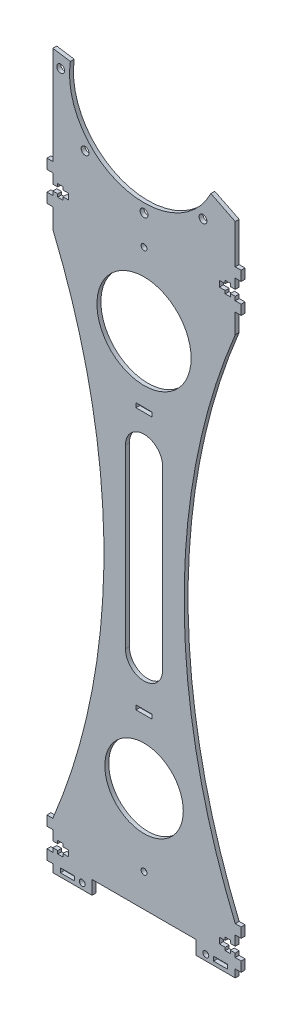
SolidWorks part; units mm, degrees
ref_plane "前视基准面" through (0, 0, 0) normal (0, 0, 1) x (1, 0, 0)
ref_plane "上视基准面" through (0, 0, 0) normal (0, 1, 0) x (1, 0, 0)
ref_plane "右视基准面" through (0, 0, 0) normal (1, 0, 0) x (0, 0, -1)
sketch "草图3" plane through (0, 0, 0) normal (0, 0, 1) x (1, 0, 0)
  line L0 (-42.5, -1.9902) -> (-42.5, -2.0902) construction
  line L2 (-46.5, -1.9902) -> (-46.5, 0.0098) construction
  line L4 (46.5, -1.9902) -> (46.5, 0.0098) construction
  line L5 (-42.5, 0.0098) -> (-35.5, 0.0098) construction
  line L6 (-42.5, 0.0098) -> (-42.5, -1.9902) construction
  line L7 (-42.5, -1.9902) -> (-35.5, -1.9902) construction
  line L8 (-35.5, 0.0098) -> (-35.5, -1.9902) construction
  line L9 (-42.5, -2.0902) -> (-42.6, -2.0902) construction
  line L10 (0, 113.3559) -> (0, 203.3559) construction
  line L11 (35.5, 0.0098) -> (42.5, 0.0098) construction
  line L12 (35.5, 0.0098) -> (35.5, -1.9902) construction
  line L13 (35.5, -1.9902) -> (42.5, -1.9902) construction
  line L14 (42.5, 0.0098) -> (42.5, -1.9902) construction
  line L15 (-46.5, 360.0098) -> (-46.5, 310.0098)
  line L17 (0, 308.5098) -> (0, 282.3462) construction
  line L18 (0, 36.4782) -> (0, 3.0098) construction
  line L19 (-42.6, -2.0902) -> (-35.4, -2.0902)
  line L20 (-42.6, -2.0902) -> (-42.6, 0.1098)
  line L21 (-42.6, 0.1098) -> (-35.4, 0.1098)
  line L22 (-35.4, -2.0902) -> (-35.4, 0.1098)
  line L23 (35.4, -2.0902) -> (35.4, 0.1098)
  line L24 (42.6, -2.0902) -> (35.4, -2.0902)
  line L25 (42.6, -2.0902) -> (42.6, 0.1098)
  line L26 (42.6, 0.1098) -> (35.4, 0.1098)
  line L27 (-46.5, 0.0098) -> (-46.5, -3.9902)
  line L28 (-46.5, -3.9902) -> (-26.5, -3.9902)
  line L29 (-26.5, -3.9902) -> (-26.5, 3.0098)
  line L30 (46.5, 0.0098) -> (46.5, -3.9902)
  line L31 (46.5, -3.9902) -> (26.5, -3.9902)
  line L32 (26.5, -3.9902) -> (26.5, 3.0098)
  line L33 (-26.5, 3.0098) -> (26.5, 3.0098)
  line L37 (46.5, 330.0098) -> (34.0612, 336.1623)
  line L38 (-46.5, 360.0098) -> (-37.5766, 358.6665)
  line L39 (-46.5, 0.0098) -> (-49.5, 0.0098)
  line L40 (-49.5, 0.0098) -> (-49.5, 5.0098)
  line L41 (-49.5, 5.0098) -> (-46.5, 5.0098)
  line L42 (-44, 7.0098) -> (-44, 5.5098)
  line L43 (-44, 10.0098) -> (-44, 11.5098)
  line L44 (-46.5, 10.0098) -> (-44, 10.0098)
  line L45 (-44, 5.5098) -> (-41.4, 5.5098)
  line L46 (-41.4, 5.5098) -> (-41.4, 7.0098)
  line L47 (-41.4, 7.0098) -> (-38.4, 7.0098)
  line L48 (-38.4, 10.0098) -> (-38.4, 7.0098)
  line L49 (-41.4, 10.0098) -> (-38.4, 10.0098)
  line L50 (-41.4, 11.5098) -> (-41.4, 10.0098)
  line L51 (-44, 11.5098) -> (-41.4, 11.5098)
  line L52 (-44, 7.0098) -> (-46.5, 7.0098)
  line L53 (-46.5, 5.0098) -> (-46.5, 7.0098)
  line L54 (-46.5, 10.0098) -> (-46.5, 15.0098)
  line L55 (-46.5, 15.0098) -> (-49.5, 15.0098)
  line L56 (-49.5, 15.0098) -> (-49.5, 20.0098)
  line L59 (49.5, 20.0098) -> (46.5, 20.0098)
  line L60 (49.5, 15.0098) -> (49.5, 20.0098)
  line L61 (46.5, 15.0098) -> (49.5, 15.0098)
  line L62 (46.5, 10.0098) -> (46.5, 15.0098)
  line L63 (46.5, 5.0098) -> (46.5, 7.0098)
  line L64 (44, 7.0098) -> (46.5, 7.0098)
  line L65 (44, 11.5098) -> (41.4, 11.5098)
  line L66 (41.4, 11.5098) -> (41.4, 10.0098)
  line L67 (41.4, 10.0098) -> (38.4, 10.0098)
  line L68 (38.4, 10.0098) -> (38.4, 7.0098)
  line L69 (41.4, 7.0098) -> (38.4, 7.0098)
  line L70 (41.4, 5.5098) -> (41.4, 7.0098)
  line L71 (44, 5.5098) -> (41.4, 5.5098)
  line L72 (46.5, 10.0098) -> (44, 10.0098)
  line L73 (44, 10.0098) -> (44, 11.5098)
  line L74 (44, 7.0098) -> (44, 5.5098)
  line L75 (49.5, 5.0098) -> (46.5, 5.0098)
  line L76 (46.5, 0.0098) -> (49.5, 0.0098)
  line L77 (49.5, 0.0098) -> (49.5, 5.0098)
  line L81 (0, 103.8804) -> (0, 76.4782) construction
  line L84 (-46.5, 290.0098) -> (-49.5, 290.0098)
  line L85 (-49.5, 290.0098) -> (-49.5, 295.0098)
  line L86 (-49.5, 295.0098) -> (-46.5, 295.0098)
  line L87 (-44, 297.0098) -> (-44, 295.5098)
  line L88 (-44, 300.0098) -> (-44, 301.5098)
  line L89 (-46.5, 300.0098) -> (-44, 300.0098)
  line L90 (-44, 295.5098) -> (-41.4, 295.5098)
  line L91 (-41.4, 295.5098) -> (-41.4, 297.0098)
  line L92 (-41.4, 297.0098) -> (-38.4, 297.0098)
  line L93 (-38.4, 300.0098) -> (-38.4, 297.0098)
  line L94 (-41.4, 300.0098) -> (-38.4, 300.0098)
  line L95 (-41.4, 301.5098) -> (-41.4, 300.0098)
  line L96 (-44, 301.5098) -> (-41.4, 301.5098)
  line L97 (-44, 297.0098) -> (-46.5, 297.0098)
  line L98 (-46.5, 295.0098) -> (-46.5, 297.0098)
  line L99 (-46.5, 300.0098) -> (-46.5, 305.0098)
  line L100 (-46.5, 305.0098) -> (-49.5, 305.0098)
  line L101 (-49.5, 305.0098) -> (-49.5, 310.0098)
  line L102 (-49.5, 310.0098) -> (-46.5, 310.0098)
  line L103 (49.5, 310.0098) -> (46.5, 310.0098)
  line L104 (49.5, 305.0098) -> (49.5, 310.0098)
  line L105 (46.5, 305.0098) -> (49.5, 305.0098)
  line L106 (46.5, 300.0098) -> (46.5, 305.0098)
  line L107 (46.5, 295.0098) -> (46.5, 297.0098)
  line L108 (44, 297.0098) -> (46.5, 297.0098)
  line L109 (44, 301.5098) -> (41.4, 301.5098)
  line L110 (41.4, 301.5098) -> (41.4, 300.0098)
  line L111 (41.4, 300.0098) -> (38.4, 300.0098)
  line L112 (38.4, 300.0098) -> (38.4, 297.0098)
  line L113 (41.4, 297.0098) -> (38.4, 297.0098)
  line L114 (41.4, 295.5098) -> (41.4, 297.0098)
  line L115 (44, 295.5098) -> (41.4, 295.5098)
  line L116 (46.5, 300.0098) -> (44, 300.0098)
  line L117 (44, 300.0098) -> (44, 301.5098)
  line L118 (44, 297.0098) -> (44, 295.5098)
  line L119 (49.5, 295.0098) -> (46.5, 295.0098)
  line L120 (49.5, 290.0098) -> (49.5, 295.0098)
  line L121 (46.5, 290.0098) -> (49.5, 290.0098)
  line L122 (46.5, 330.0098) -> (46.5, 310.0098)
  line L123 (46.5, 290.0098) -> (46.5, 280.0098)
  line L124 (-46.5, 290.0098) -> (-46.5, 280.0098)
  line L127 (-49.5, 20.0098) -> (-46.5, 20.0098)
  line L129 (-9.4755, 113.3559) -> (-9.4755, 203.3559)
  line L130 (9.4755, 113.3559) -> (9.4755, 203.3559)
  line L132 (0, 212.8314) -> (0, 234.3433) construction
  line L133 (4.1, 91.2793) -> (-4.1, 91.2793)
  line L134 (4.1, 91.2793) -> (4.1, 89.0793)
  line L135 (4.1, 89.0793) -> (-4.1, 89.0793)
  line L136 (-4.1, 91.2793) -> (-4.1, 89.0793)
  line L137 (4.1, 91.2793) -> (-4.1, 89.0793) construction
  line L138 (4.1, 89.0793) -> (-4.1, 91.2793) construction
  line L140 (4.1, 224.6874) -> (-4.1, 224.6874)
  line L141 (4.1, 224.6874) -> (4.1, 222.4874)
  line L142 (4.1, 222.4874) -> (-4.1, 222.4874)
  line L143 (-4.1, 224.6874) -> (-4.1, 222.4874)
  line L144 (4.1, 224.6874) -> (-4.1, 222.4874) construction
  line L145 (4.1, 222.4874) -> (-4.1, 224.6874) construction
  circle A0 centre (-31.5, -0.9902) radius 1.5
  circle A1 centre (31.5, -0.9902) radius 1.5
  circle A4 centre (0, 310.5098) radius 2
  circle A5 centre (-30.052, 322.9577) radius 2
  circle A6 centre (-42.5, 353.0098) radius 2
  circle A11 centre (30.052, 322.9577) radius 2
  arc A12 (-37.5766, 358.6665) -> (34.0612, 336.1623) centre (0, 353.0098) ccw
  arc A15 (-46.5, 280.0098) -> (-46.5, 20.0098) centre (-357.8256, 150.0098) cw
  arc A16 (46.5, 280.0098) -> (46.5, 20.0098) centre (357.8256, 150.0098) ccw
  circle A17 centre (0, 258.3448) radius 24.0015
  circle A18 centre (0, 56.4782) radius 20
  arc A19 (-9.4755, 113.3559) -> (9.4755, 113.3559) centre (0, 113.3559) ccw
  arc A20 (9.4755, 203.3559) -> (-9.4755, 203.3559) centre (0, 203.3559) ccw
  circle A21 centre (0, 19.744) radius 1.5
  circle A22 centre (0, 295.428) radius 1.5
  point P56 (0, 158.3559)
  point P143 (0, 90.1793)
  point P151 (0, 223.5874)
extrude "凸台-拉伸1" add sketch "草图3" along normal blind 2
sketch "草图4" plane through (46.5, 0, 0) normal (1, 0, 0) x (0, 0, -1)
  line L0 (-2, 10.0098) -> (0, 7.0098)
  circle A0 centre (-1, 8.5098) radius 1.5
sketch "草图5" plane through (-46.5, 0, 0) normal (-1, 0, 0) x (0, 0, 1)
  line L0 (0, 10.0098) -> (2, 7.0098)
  circle A0 centre (1, 8.5098) radius 1.5
sketch "草图6" plane through (46.5, 0, 0) normal (1, 0, 0) x (0, 0, -1)
  line L0 (-2, 300.0098) -> (0, 297.0098)
  circle A0 centre (-1, 298.5098) radius 1.5
sketch "草图7" plane through (-46.5, 0, 0) normal (-1, 0, 0) x (0, 0, 1)
  line L0 (0, 300.0098) -> (2, 297.0098)
  circle A0 centre (1, 298.5098) radius 1.5
